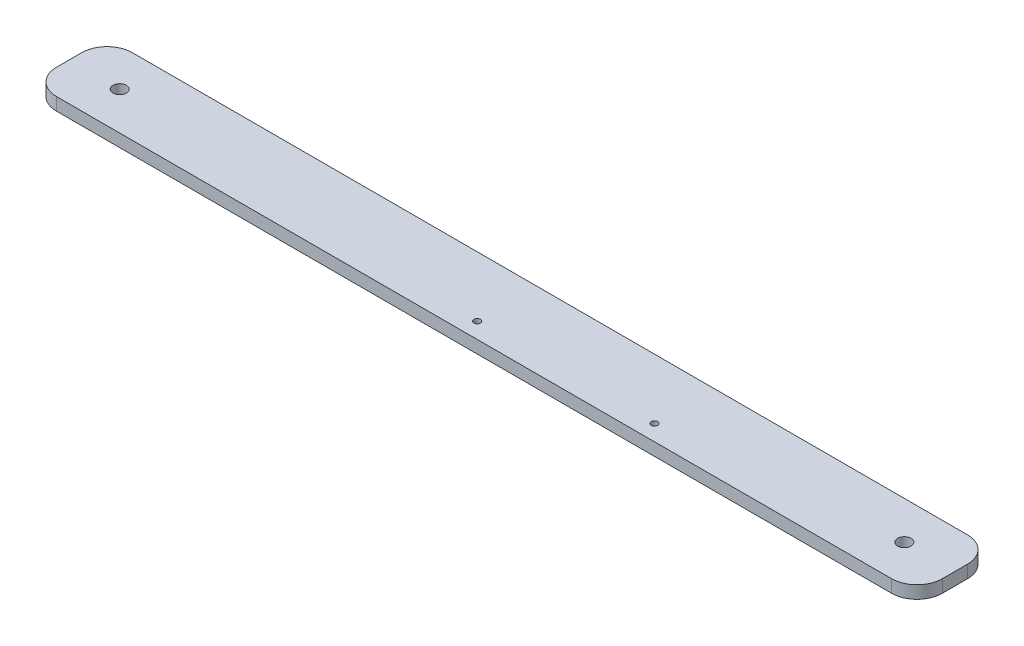
SolidWorks part; units mm, degrees
ref_plane "Front Plane" through (0, 0, 0) normal (0, 0, 1) x (1, 0, 0)
ref_plane "Top Plane" through (0, 0, 0) normal (0, 1, 0) x (1, 0, 0)
ref_plane "Right Plane" through (0, 0, 0) normal (1, 0, 0) x (0, 0, -1)
sketch "Sketch1" plane through (0, 0, 0) normal (0, 1, 0) x (1, 0, 0)
  line L1 (0, 0) -> (444.5, 0)
  line L2 (0, 0) -> (0, 38.1)
  line L3 (0, 38.1) -> (444.5, 38.1)
  line L4 (444.5, 0) -> (444.5, 38.1)
  dimension "D1" = 444.5
  dimension "D2" = 38.1
extrude "Boss-Extrude1" add sketch "Sketch1" along normal blind 6.35
fillet "Fillet1" radius 12.7 1 edges at (0, 3.175, 0)
fillet "Fillet2" radius 12.7 1 edges at (0, 3.175, -38.1)
fillet "Fillet3" radius 12.7 1 edges at (444.5, 3.175, -38.1)
fillet "Fillet4" radius 12.7 1 edges at (444.5, 3.175, 0)
sketch "Sketch2" plane through (0, 6.35, 0) normal (0, 1, 0) x (1, 0, 0)
  line L0 (431.8, 38.1) -> (12.7, 38.1) construction
  line L1 (0, 25.4) -> (0, 12.7) construction
  circle A0 centre (25.4, 19.05) radius 3.3782
  dimension "D1" = 19.05
  dimension "D2" = 25.4
extrude "Cut-Extrude1" cut sketch "Sketch2" against normal through all
sketch "Sketch4" plane through (0, 6.35, 0) normal (0, 1, 0) x (1, 0, 0)
  line L0 (431.8, 38.1) -> (12.7, 38.1) construction
  line L1 (444.5, 12.7) -> (444.5, 25.4) construction
  circle A0 centre (419.1, 19.05) radius 3.3782
  dimension "D1" = 19.05
  dimension "D2" = 25.4
extrude "Cut-Extrude2" cut sketch "Sketch4" against normal through all
hole_wizard "CSK for #4 Flat Head Machine Screw1" positions "Sketch6" profile "Sketch5" countersink size "#4" standard "ANSI Inch" end condition through all
sketch "Sketch6" plane through (0, 0, 0) normal (0, -1, 0) x (-1, 0, 0)
  point P0 (-304.8, 7.9375)
  point P3 (-215.9, 7.9375)
sketch "Sketch5" plane through (304.8, 0, -7.9375) normal (1, 0, 0) x (0, 0, -1)
  line L0 (0, 0) -> (0, 6.35)
  line L1 (0, 6.35) -> (1.6319, 6.35)
  line L2 (1.6319, 6.35) -> (1.6319, 1.4098)
  line L3 (1.6319, 1.4098) -> (2.8575, 0)
  line L5 (2.8575, 0) -> (0, 0)
  line L6 (-1.6319, 1.4098) -> (-2.8575, 0) construction
  line L11 (0, -6.35) -> (0, 107.95) construction
  dimension "Thru Hole Dia." = 3.2639
  dimension "Thru Hole Depth" = 6.35
  dimension "Near C'Sink Dia." = 5.715
  dimension "Near C'Sink Angle" = 82
